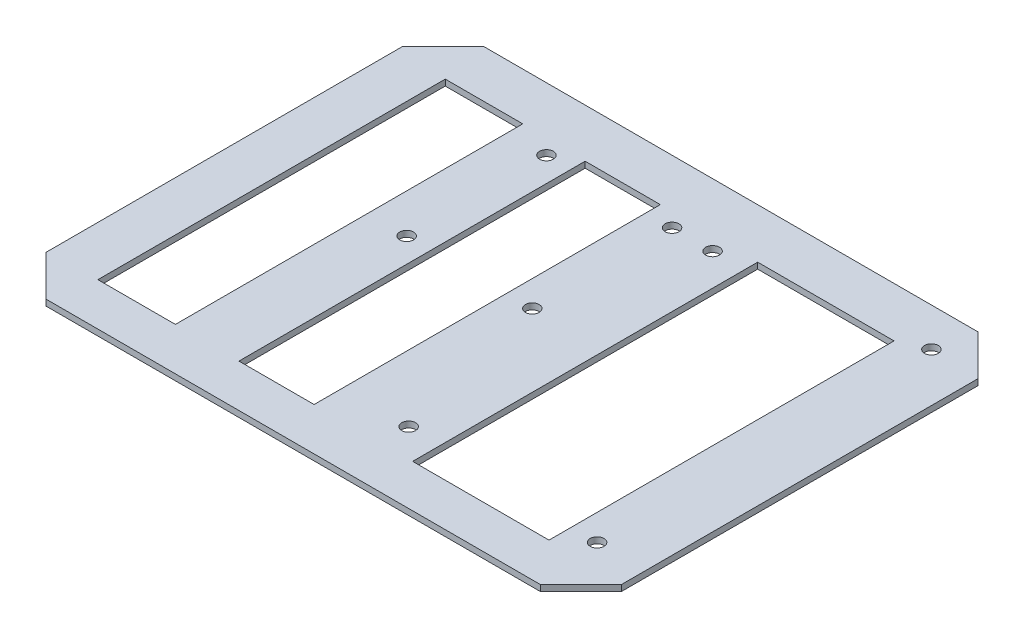
SolidWorks part; units mm, degrees
ref_plane "前视基准面" through (0, 0, 0) normal (0, 0, 1) x (1, 0, 0)
ref_plane "上视基准面" through (0, 0, 0) normal (0, 1, 0) x (1, 0, 0)
ref_plane "右视基准面" through (0, 0, 0) normal (1, 0, 0) x (0, 0, -1)
sketch "Sketch1" plane through (0, 0, 0) normal (0, 1, 0) x (1, 0, 0)
  line L1 (-71, -54) -> (71, -54)
  line L2 (-71, -54) -> (-71, 54)
  line L3 (-71, 54) -> (71, 54)
  line L4 (71, -54) -> (71, 54)
  line L5 (-71, -54) -> (71, 54) construction
  line L6 (-71, 54) -> (71, -54) construction
  point P0 (0, 0)
  dimension "D1" = 142
  dimension "D2" = 108
extrude "Boss-Extrude1" add sketch "Sketch1" along normal blind 1.5
chamfer "Chamfer1" distance 10 angle 45 4 edges at (71, 0.75, -54) (-71, 0.75, -54) (-71, 0.75, 54) (71, 0.75, 54)
sketch "Sketch2" plane through (0, 1.5, 0) normal (0, 1, 0) x (1, 0, 0)
  line L0 (71, -44) -> (71, 44) construction
  line L2 (-61, -54) -> (61, -54) construction
  line L3 (59, 44.5) -> (59, -38) construction
  line L4 (11, 38.5) -> (11, -36.5) construction
  circle A0 centre (59, 44.5) radius 1.7
  circle A1 centre (11, 38.5) radius 1.7
  circle A2 centre (11, -36.5) radius 1.7
  circle A3 centre (59, -38) radius 1.7
  dimension "D1" = 3.4
  dimension "D2" = 12
  dimension "D3" = 16
  dimension "D4" = 82.5
  dimension "D5" = 48
  dimension "D6" = 1.5
  dimension "D7" = 75
extrude "Cut-Extrude1" cut sketch "Sketch2" against normal up to next
sketch "Sketch3" plane through (0, 1.5, 0) normal (0, 1, 0) x (1, 0, 0)
  line L1 (-30, 38.5) -> (1, 38.5) construction
  line L2 (-30, 38.5) -> (-30, 4) construction
  line L3 (-30, 4) -> (1, 4) construction
  line L4 (1, 38.5) -> (1, 4) construction
  line L5 (1, 38.5) -> (11, 38.5) construction
  circle A0 centre (-30, 38.5) radius 1.7
  circle A1 centre (1, 38.5) radius 1.7
  circle A2 centre (1, 4) radius 1.7
  circle A3 centre (-30, 4) radius 1.7
  dimension "D1" = 3.4
  dimension "D2" = 31
  dimension "D3" = 34.5
  dimension "D4" = 10
extrude "Cut-Extrude2" cut sketch "Sketch3" against normal up to next
sketch "Sketch4" plane through (0, 1.5, 0) normal (0, 1, 0) x (1, 0, 0)
  line L1 (-58.7573, 42.288) -> (-39.627, 42.288)
  line L2 (-58.7573, 42.288) -> (-58.7573, -43.4387)
  line L3 (-58.7573, -43.4387) -> (-39.627, -43.4387)
  line L4 (-39.627, 42.288) -> (-39.627, -43.4387)
  line L9 (18.9145, 41.7126) -> (52.5723, 41.7126)
  line L10 (18.9145, 41.7126) -> (18.9145, -43.4387)
  line L11 (18.9145, -43.4387) -> (52.5723, -43.4387)
  line L12 (52.5723, 41.7126) -> (52.5723, -43.4387)
  line L13 (-23.9488, 42.0003) -> (-5.3939, 42.0003)
  line L14 (-23.9488, 42.0003) -> (-23.9488, -43.4387)
  line L15 (-23.9488, -43.4387) -> (-5.3939, -43.4387)
  line L16 (-5.3939, 42.0003) -> (-5.3939, -43.4387)
extrude "Cut-Extrude3" cut sketch "Sketch4" against normal up to next
